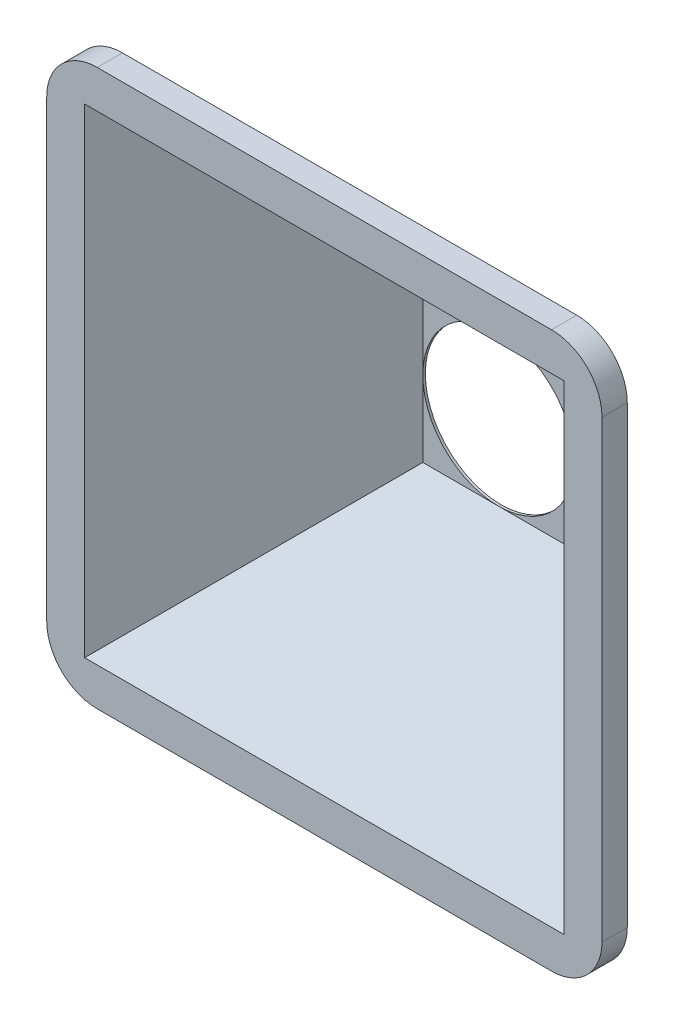
SolidWorks part; units mm, degrees
ref_plane "정면" through (0, 0, 0) normal (0, 0, 1) x (1, 0, 0)
ref_plane "윗면" through (0, 0, 0) normal (0, 1, 0) x (1, 0, 0)
ref_plane "우측면" through (0, 0, 0) normal (1, 0, 0) x (0, 0, -1)
sketch "스케치1" plane through (0, 0, 0) normal (0, 0, 1) x (1, 0, 0)
  line L1 (200, -200) -> (-200, -200)
  line L2 (200, -200) -> (200, 200)
  line L3 (200, 200) -> (-200, 200)
  line L4 (-200, -200) -> (-200, 200)
  line L5 (200, -200) -> (-200, 200) construction
  line L6 (200, 200) -> (-200, -200) construction
  point P0 (0, 0)
ref_plane "평면1" through (0, 0, 300) normal (0, 0, 1) x (1, 0, 0)
sketch "스케치2" plane through (0, 0, 300) normal (0, 0, 1) x (1, 0, 0)
  line L1 (500, -500) -> (-500, -500)
  line L2 (500, -500) -> (500, 500)
  line L3 (500, 500) -> (-500, 500)
  line L4 (-500, -500) -> (-500, 500)
  line L5 (500, -500) -> (-500, 500) construction
  line L6 (500, 500) -> (-500, -500) construction
  point P0 (0, 0)
loft "로프트1" add profiles "스케치1", "스케치2"
sketch "스케치3" plane through (0, 0, 300) normal (0, 0, 1) x (1, 0, 0)
  line L1 (550.0016, -550.1901) -> (-550.0016, -550.1901)
  line L2 (550.0016, -550.1901) -> (550.0016, 550.1901)
  line L3 (550.0016, 550.1901) -> (-550.0016, 550.1901)
  line L4 (-550.0016, -550.1901) -> (-550.0016, 550.1901)
  line L5 (550.0016, -550.1901) -> (-550.0016, 550.1901) construction
  line L6 (550.0016, 550.1901) -> (-550.0016, -550.1901) construction
  point P0 (0, 0)
extrude "보스-돌출1" add sketch "스케치3" along normal blind 50
fillet "필렛1" radius 100 1 edges at (-550.0016, -550.1901, 325)
fillet "필렛3" radius 100 1 edges at (550.0016, -550.1901, 325)
fillet "필렛4" radius 100 1 edges at (-550.0016, 550.1901, 325)
fillet "필렛5" radius 100 1 edges at (550.0016, 550.1901, 325)
sketch "스케치4" plane through (0, 0, 350) normal (0, 0, 1) x (1, 0, 0)
  line L1 (475, -475) -> (-475, -475)
  line L2 (475, -475) -> (475, 475)
  line L3 (475, 475) -> (-475, 475)
  line L4 (-475, -475) -> (-475, 475)
  line L5 (475, -475) -> (-475, 475) construction
  line L6 (475, 475) -> (-475, -475) construction
  point P0 (0, 0)
sketch "스케치5" plane through (0, 0, 0) normal (0, 0, -1) x (-1, 0, 0)
  line L1 (150, -150) -> (-150, -150)
  line L2 (150, -150) -> (150, 150)
  line L3 (150, 150) -> (-150, 150)
  line L4 (-150, -150) -> (-150, 150)
  line L5 (150, -150) -> (-150, 150) construction
  line L6 (150, 150) -> (-150, -150) construction
  line L7 (-475, 475) -> (475, -475) construction
  dimension "D1" = 150
  dimension "D2" = 150
loft "컷-로프트1" cut profiles "스케치5", "스케치4"
sketch "스케치6" plane through (0, 0, 0) normal (0, 0, 1) x (1, 0, 0)
  line L1 (150, -150) -> (-150, -150)
  line L2 (150, -150) -> (150, 150)
  line L3 (150, 150) -> (-150, 150)
  line L4 (-150, -150) -> (-150, 150)
  line L5 (150, -150) -> (-150, 150) construction
  line L6 (150, 150) -> (-150, -150) construction
  circle A0 centre (0, 0) radius 150
extrude "보스-돌출2" add sketch "스케치6" along normal blind 5 separate body contours A0 L3 L4 | A0 L4 L1 | A0 L2 L3 | A0 L1 L2
